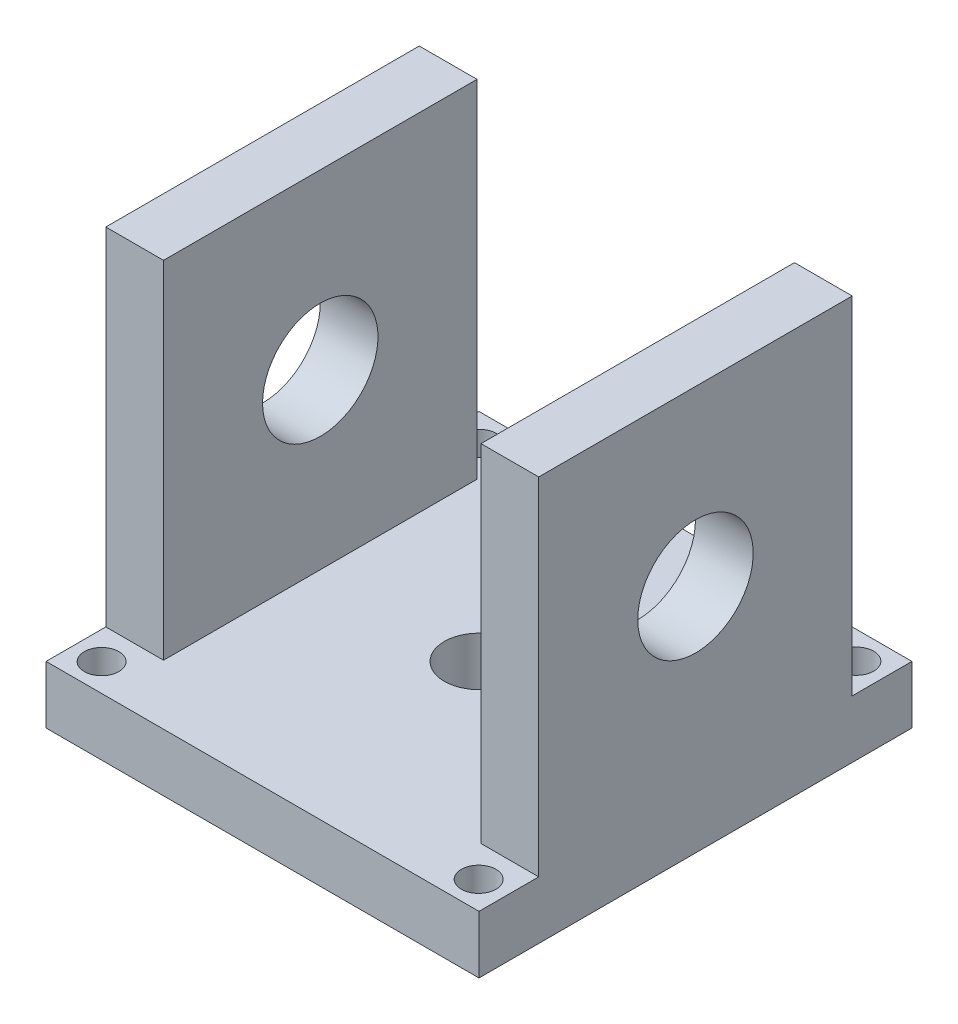
SolidWorks part; units mm, degrees
ref_plane "Front Plane" through (0, 0, 0) normal (0, 0, 1) x (1, 0, 0)
ref_plane "Top Plane" through (0, 0, 0) normal (0, 1, 0) x (1, 0, 0)
ref_plane "Right Plane" through (0, 0, 0) normal (1, 0, 0) x (0, 0, -1)
sketch "Sketch1" plane through (0, 0, 0) normal (0, 1, 0) x (1, 0, 0)
  line L0 (0, 0) -> (0, 37.5) construction
  line L1 (37.5, 37.5) -> (-37.5, 37.5)
  line L2 (37.5, 37.5) -> (37.5, -37.5)
  line L3 (37.5, -37.5) -> (-37.5, -37.5)
  line L4 (-37.5, 37.5) -> (-37.5, -37.5)
  line L5 (0, 0) -> (-37.5, 0) construction
  circle A0 centre (-32.66, 32.72) radius 3
  circle A1 centre (32.66, 32.72) radius 3
  circle A2 centre (32.66, -32.72) radius 3
  circle A3 centre (-32.66, -32.72) radius 3
  circle A4 centre (0, 0) radius 6
  point P0 (0, 0)
  point P11 (0, -37.5)
  dimension "D3" = 6
  dimension "D5" = 12
  dimension "D1" = 4.84
  dimension "D2" = 75
  dimension "D4" = 75
  dimension "D6" = 65.44
extrude "Boss-Extrude1" add sketch "Sketch1" along normal blind 10
sketch "Sketch2" plane through (0, 10, 0) normal (0, 1, 0) x (1, 0, 0)
  line L0 (-37.5, 37.5) -> (-37.5, -37.5) construction
  line L1 (-37.5, 27.1541) -> (-27.5, 27.1541)
  line L2 (-37.5, 27.1541) -> (-37.5, -27.1541)
  line L3 (0, 0) -> (0, 27.1541) construction
  line L4 (-27.5, 27.1541) -> (-27.5, -27.1541)
  line L5 (0, 0) -> (-23.3341, 0) construction
  line L6 (-37.5, -27.1541) -> (-27.5, -27.1541)
  line L7 (37.5, -27.1541) -> (27.5, -27.1541)
  line L8 (27.5, 27.1541) -> (27.5, -27.1541)
  line L9 (37.5, 27.1541) -> (37.5, -27.1541)
  line L10 (37.5, 27.1541) -> (27.5, 27.1541)
  point P12 (-27.5, 0)
  point P13 (-37.5, 0)
  point P17 (37.5, 0)
  point P18 (27.5, 0)
  dimension "D1" = 10
extrude "Boss-Extrude2" add sketch "Sketch2" along normal blind 60
sketch "Sketch3" plane through (-37.5, 0, 0) normal (-1, 0, 0) x (0, 0, 1)
  line L0 (0, 70) -> (0, 0) construction
  line L1 (-27.1541, 70) -> (27.1541, 70) construction
  line L2 (-27.1541, 40) -> (27.1541, 40) construction
  line L3 (-27.1541, 70) -> (-27.1541, 10) construction
  line L4 (27.1541, 70) -> (27.1541, 10) construction
  circle A0 centre (0, 40) radius 10
  dimension "D1" = 20
extrude "Cut-Extrude1" cut sketch "Sketch3" against normal through all both and the other way through all
